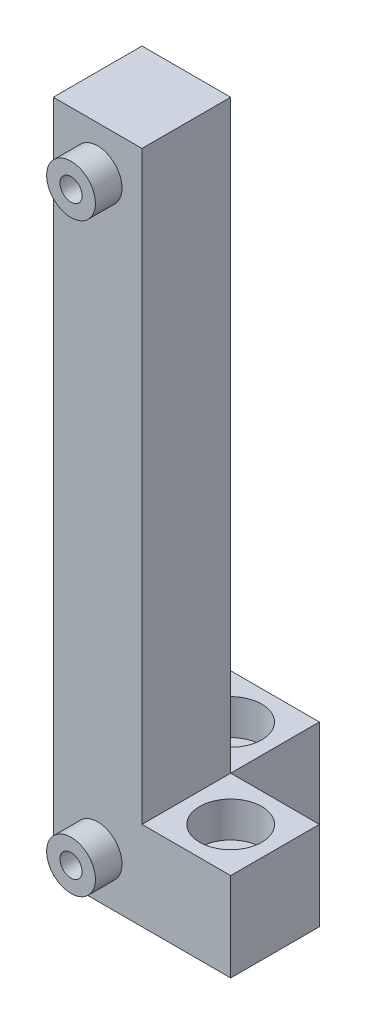
SolidWorks part; units mm, degrees
ref_plane "Plan de face" through (0, 0, 0) normal (0, 0, 1) x (1, 0, 0)
ref_plane "Plan de dessus" through (0, 0, 0) normal (0, 1, 0) x (1, 0, 0)
ref_plane "Plan de droite" through (0, 0, 0) normal (1, 0, 0) x (0, 0, -1)
sketch "Esquisse1" plane through (0, 0, 0) normal (0, 0, 1) x (1, 0, 0)
  line L0 (0, 76) -> (10, 76)
  line L1 (10, 76) -> (10, 10)
  line L2 (10, 10) -> (20, 10)
  line L3 (20, 10) -> (20, 0)
  line L4 (20, 0) -> (0, 0)
  line L5 (0, 0) -> (0, 76)
  dimension "D1" = 76
  dimension "D2" = 10
  dimension "D3" = 10
  dimension "D4" = 20
extrude "Boss.-Extru.1" add sketch "Esquisse1" along normal blind 10
sketch "Esquisse2" plane through (0, 0, 10) normal (0, 0, 1) x (1, 0, 0)
  line L0 (10, 76) -> (0, 76) construction
  line L1 (0, 0) -> (20, 0) construction
  circle A0 centre (5, 71) radius 2.75
  circle A1 centre (5, 5) radius 2.75
  point P7 (5, 76)
  dimension "D1" = 5.5
  dimension "D2" = 5
  dimension "D3" = 5
extrude "Boss.-Extru.2" add sketch "Esquisse2" along normal blind 3
sketch "Esquisse3" plane through (0, 0, 13) normal (0, 0, 1) x (1, 0, 0)
  circle A0 centre (5, 71) radius 1.25
  circle A1 centre (5, 5) radius 1.25
  dimension "D1" = 2.5
extrude "Enlèv. mat.-Extru.1" cut sketch "Esquisse3" against normal blind 8
sketch "Esquisse4" plane through (0, 0, 0) normal (0, 0, -1) x (-1, 0, 0)
  line L1 (-10, 10) -> (0, 10)
  line L2 (-10, 10) -> (-10, 0)
  line L3 (-10, 0) -> (0, 0)
  line L4 (0, 10) -> (0, 0)
extrude "Boss.-Extru.3" add sketch "Esquisse4" along normal blind 10
sketch "Esquisse5" plane through (0, 10, 0) normal (0, 1, 0) x (1, 0, 0)
  line L0 (20, -10) -> (10, -10) construction
  line L1 (20, -10) -> (20, 0) construction
  line L2 (0, 10) -> (10, 10) construction
  line L3 (10, 10) -> (10, 0) construction
  circle A0 centre (15, -5) radius 1.75
  circle A1 centre (5, 5) radius 1.75
  point P7 (15, -10)
  point P11 (20, -5)
  point P15 (5, 10)
  point P19 (10, 5)
  dimension "D1" = 3.5
extrude "Enlèv. mat.-Extru.2" cut sketch "Esquisse5" against normal up to next
sketch "Esquisse6" plane through (0, 10, 0) normal (0, 1, 0) x (1, 0, 0)
  circle A0 centre (15, -5) radius 3.5
  circle A1 centre (5, 5) radius 3.5
  dimension "D1" = 7
extrude "Enlèv. mat.-Extru.3" cut sketch "Esquisse6" against normal blind 4
